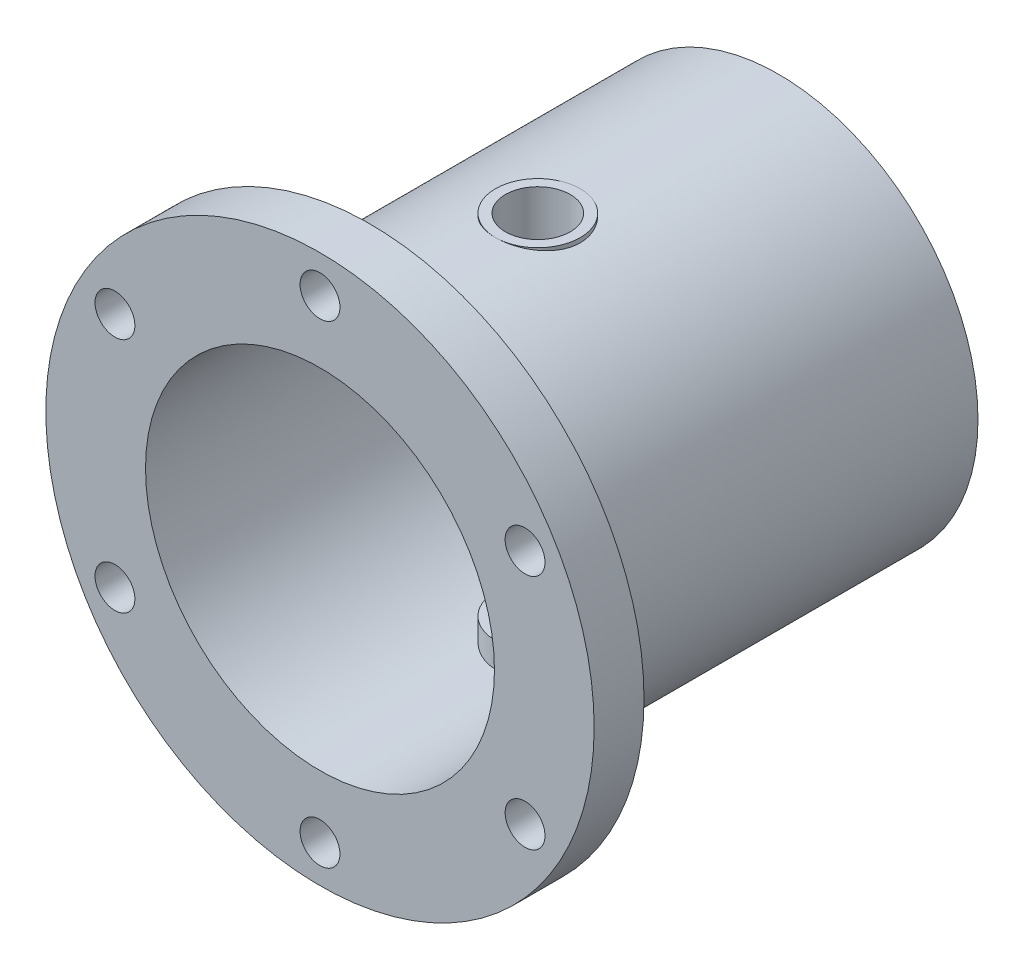
SolidWorks part; units mm, degrees
ref_plane "Front Plane" through (0, 0, 0) normal (0, 0, 1) x (1, 0, 0)
ref_plane "Top Plane" through (0, 0, 0) normal (0, 1, 0) x (1, 0, 0)
ref_plane "Right Plane" through (0, 0, 0) normal (1, 0, 0) x (0, 0, -1)
sketch "Sketch1" plane through (0, 0, 0) normal (0, 0, 1) x (1, 0, 0)
  circle A0 centre (0, 0) radius 40
  circle A1 centre (0, 0) radius 35
  dimension "D1" = 80
  dimension "D2" = 70
extrude "Boss-Extrude1" add sketch "Sketch1" along normal blind 92
sketch "Sketch2" plane through (0, 0, 0) normal (0, 0, -1) x (-1, 0, 0)
  circle A0 centre (0, 0) radius 13
  circle A1 centre (0, 0) radius 40
  circle A2 centre (0, 0) radius 40 construction
  dimension "D1" = 26
extrude "Boss-Extrude2" add sketch "Sketch2" against normal blind 6
sketch "Sketch3" plane through (0, 0, 0) normal (0, 1, 0) x (1, 0, 0)
  circle A0 centre (0, -48.2979) radius 6.5
  dimension "D2" = 13
  dimension "D1" = 48.2979
extrude "Cut-Extrude1" cut sketch "Sketch3" against normal through all both and the other way through all
ref_plane "Plane1" through (0, -40, 0) normal (0, -1, 0) x (-1, 0, 0)
sketch "Sketch4" plane through (0, -40, 0) normal (0, -1, 0) x (-1, 0, 0)
  circle A0 centre (0, -48.2979) radius 8.5
  circle A1 centre (0, -48.2979) radius 6.5
  circle A2 centre (0, -48.2979) radius 6.5 construction
  dimension "D1" = 17
extrude "Boss-Extrude3" add sketch "Sketch4" against normal blind 10
ref_plane "Plane2" through (0, 40, 0) normal (0, 1, 0) x (1, 0, 0)
sketch "Sketch5" plane through (0, 40, 0) normal (0, 1, 0) x (1, 0, 0)
  circle A0 centre (0, -48.2979) radius 8.5
  circle A1 centre (0, -48.2979) radius 6.5
  circle A2 centre (0, -48.2979) radius 6.5 construction
  dimension "D1" = 17
extrude "Boss-Extrude4" add sketch "Sketch5" against normal blind 10
sketch "Sketch7" plane through (0, 0, 92) normal (0, 0, 1) x (1, 0, 0)
  circle A0 centre (0, 0) radius 55
  circle A1 centre (0, 0) radius 35
  dimension "D1" = 110
  dimension "D2" = 70
extrude "Boss-Extrude5" add sketch "Sketch7" against normal blind 10
sketch "Sketch8" plane through (0, 0, 92) normal (0, 0, 1) x (1, 0, 0)
  circle A0 centre (0, 0) radius 47.5 construction
  circle A1 centre (0, 47.5) radius 4
  circle A2 centre (41.1362, 23.75) radius 4
  circle A3 centre (0, 0) radius 47.5 construction
  circle A4 centre (41.1362, -23.75) radius 4
  circle A5 centre (0, 0) radius 47.5 construction
  circle A6 centre (0, -47.5) radius 4
  circle A7 centre (0, 0) radius 47.5 construction
  circle A8 centre (-41.1362, -23.75) radius 4
  circle A9 centre (0, 0) radius 47.5 construction
  circle A10 centre (-41.1362, 23.75) radius 4
  circle A11 centre (0, 0) radius 47.5 construction
  point P23 (0, 0)
  dimension "D1" = 8
  dimension "D2" = 95
  dimension "D3" = 6
extrude "Cut-Extrude2" cut sketch "Sketch8" against normal up to next contours A1 | A10 | A8 | A6 | A4 | A2
